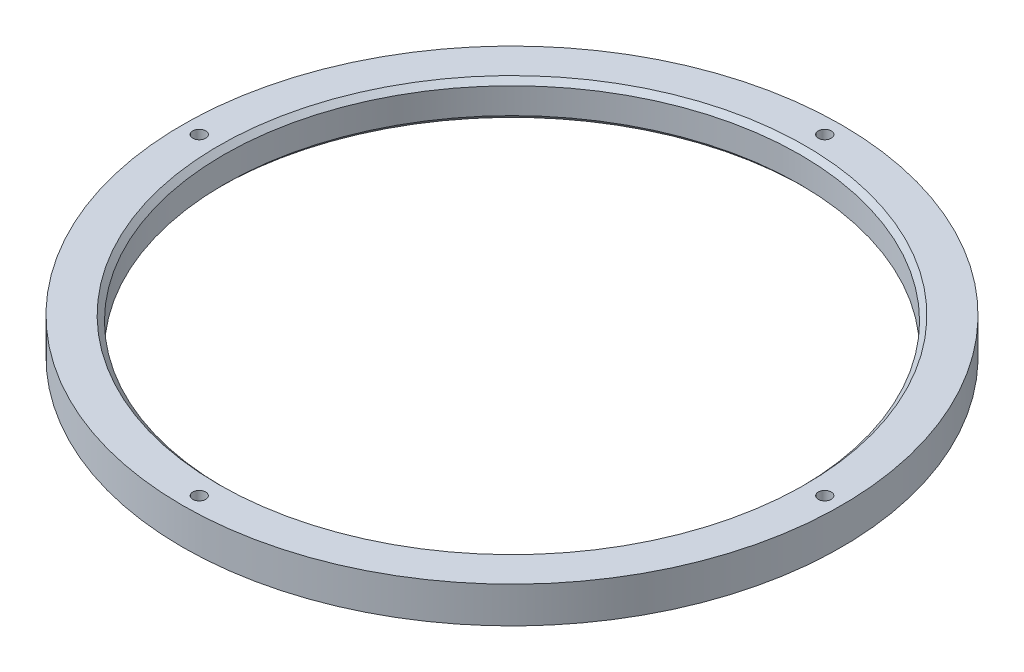
SolidWorks part; units mm, degrees
material "AISI 304"
ref_plane "Front Plane" through (0, 0, 0) normal (0, 0, 1) x (1, 0, 0)
ref_plane "Top Plane" through (0, 0, 0) normal (0, 1, 0) x (1, 0, 0)
ref_plane "Right Plane" through (0, 0, 0) normal (1, 0, 0) x (0, 0, -1)
sketch "Sketch1" plane through (0, 0, 0) normal (0, 1, 0) x (1, 0, 0)
  line L0 (0, 136.0724) -> (0, -140.419) construction
  circle A0 centre (0, 0) radius 127.5
  circle A1 centre (0, 0) radius 121 construction
  circle A2 centre (0, 0) radius 111.5
  circle A3 centre (0, 121) radius 2.5
  circle A4 centre (121, 0) radius 2.5
  circle A5 centre (0, -121) radius 2.5
  circle A6 centre (-121, 0) radius 2.5
  point P18 (0, 0)
  dimension "D1" = 255
  dimension "D2" = 242
  dimension "D3" = 223
  dimension "D4" = 5
  dimension "D5" = 4
extrude "Boss-Extrude1" add sketch "Sketch1" along normal blind 14
chamfer "Chamfer1" distance 2 angle 45 2 edges at (0, 0, 111.5) (0, 14, 111.5)
